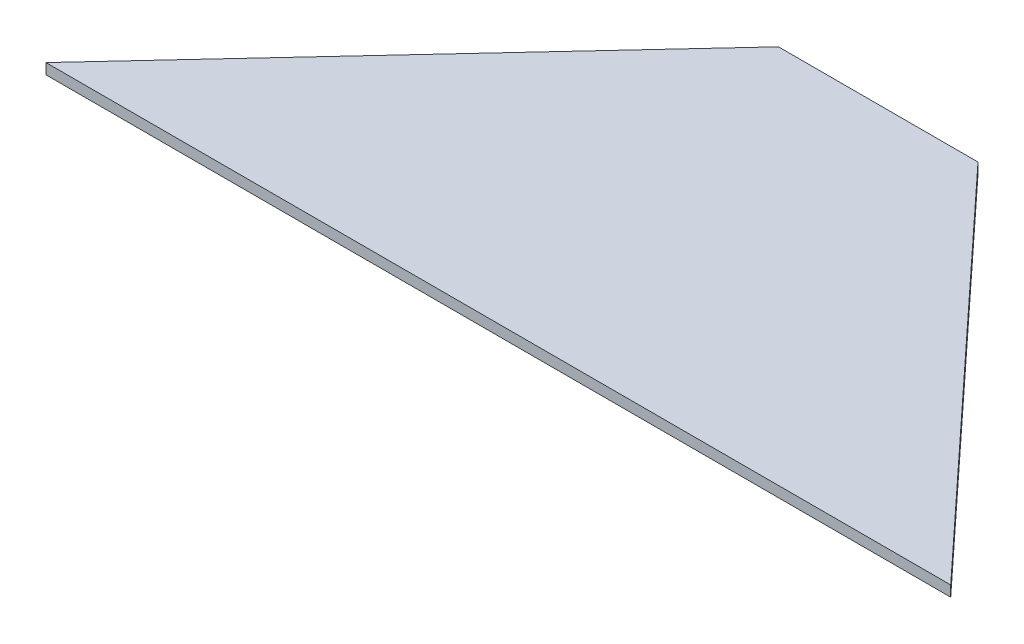
SolidWorks part; units mm, degrees
material "Сосна"
ref_plane "Спереди" through (0, 0, 0) normal (0, 0, 1) x (1, 0, 0)
ref_plane "Сверху" through (0, 0, 0) normal (0, 1, 0) x (1, 0, 0)
ref_plane "Справа" through (0, 0, 0) normal (1, 0, 0) x (0, 0, -1)
sketch3d "Трехмерный эскиз1"
  line L8 (-117.416, 10, -211.1189) -> (222.584, 10, -211.1189)
  line L9 (222.584, 10, -211.1189) -> (90.084, 10, -353.8809)
  line L10 (90.084, 10, -353.8809) -> (15.084, 10, -353.8809)
  line L11 (15.084, 10, -353.8809) -> (-117.416, 10, -211.1189)
  dimension "D8" = 194.7749
  dimension "D9" = 194.7749
  dimension "D10" = 340
  dimension "D11" = 75
extrude "Бобышка-Вытянуть1" add sketch "Трехмерный эскиз1" along direction (0, 1, 0) on the side of the normal blind 4
